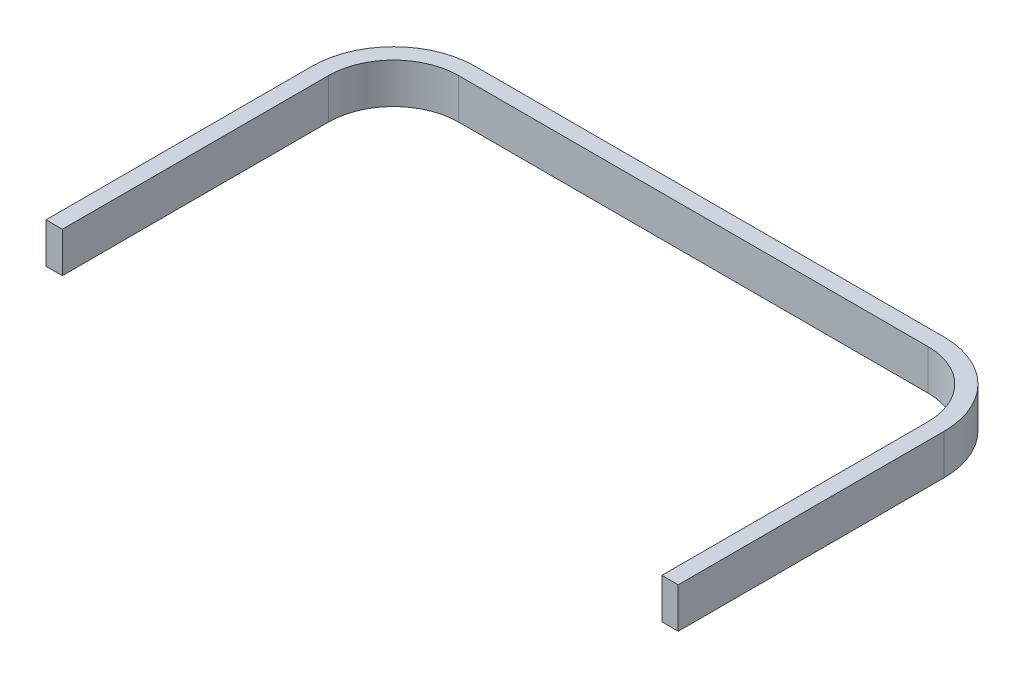
SolidWorks part; units mm, degrees
ref_plane "Front Plane" through (0, 0, 0) normal (0, 0, 1) x (1, 0, 0)
ref_plane "Top Plane" through (0, 0, 0) normal (0, 1, 0) x (1, 0, 0)
ref_plane "Right Plane" through (0, 0, 0) normal (1, 0, 0) x (0, 0, -1)
sketch "Sketch1" plane through (0, 0, 0) normal (0, 1, 0) x (1, 0, 0)
  line L0 (0, 0) -> (0, 762.8492) construction
  line L1 (0, 762.8492) -> (-609.6, 762.8492)
  line L2 (-800.1, 572.3492) -> (-800.1, -118.948)
  arc A0 (-609.6, 762.8492) -> (-800.1, 572.3492) centre (-609.6, 572.3492) ccw
  point P7 (-800.1, 762.8492)
  dimension "D2" = 190.5
  dimension "D1" = 800.1
ref_plane "Plane1" through (-800.1, 0, 118.948) normal (0, 0, 1) x (1, 0, 0)
sketch "Sketch2" plane through (-800.1, 0, 118.948) normal (0, 0, 1) x (1, 0, 0)
  line L1 (-21.224, -52.3076) -> (21.224, -52.3076)
  line L2 (-21.224, -52.3076) -> (-21.224, 52.3076)
  line L3 (-21.224, 52.3076) -> (21.224, 52.3076)
  line L4 (21.224, -52.3076) -> (21.224, 52.3076)
  line L5 (-21.224, -52.3076) -> (21.224, 52.3076) construction
  line L6 (-21.224, 52.3076) -> (21.224, -52.3076) construction
  point P0 (0, 0)
sweep "Sweep1" add profiles "Sketch2" path "Sketch1"
mirror "Mirror1" about plane through (0, 0, 37.2508) normal (1, 0, 0) of "Sweep1"
